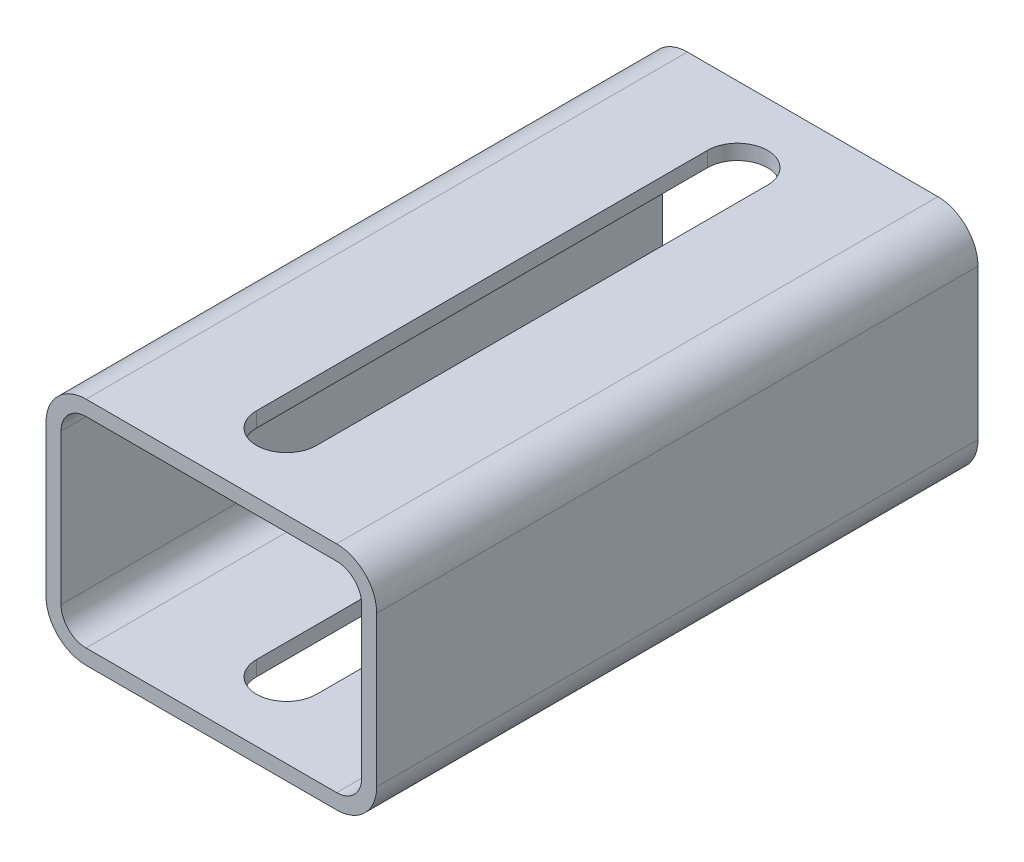
SolidWorks part; units mm, degrees
ref_plane "Front Plane" through (0, 0, 0) normal (0, 0, 1) x (1, 0, 0)
ref_plane "Top Plane" through (0, 0, 0) normal (0, 1, 0) x (1, 0, 0)
ref_plane "Right Plane" through (0, 0, 0) normal (1, 0, 0) x (0, 0, -1)
sketch "Sketch1" plane through (0, 0, 0) normal (0, 0, 1) x (1, 0, 0)
  line L1 (-25, 20) -> (25, 20)
  line L2 (-30, 15) -> (-30, -15)
  line L3 (-25, -20) -> (25, -20)
  line L4 (30, 15) -> (30, -15)
  line L5 (-30, 20) -> (30, -20) construction
  line L6 (-30, -20) -> (30, 20) construction
  arc A0 (-30, -15) -> (-25, -20) centre (-25, -15) ccw
  arc A1 (25, -20) -> (30, -15) centre (25, -15) ccw
  arc A2 (25, 20) -> (30, 15) centre (25, 15) cw
  arc A3 (-25, 20) -> (-30, 15) centre (-25, 15) ccw
  point P0 (0, 0)
  dimension "D3" = 5
  dimension "Height" = 40
  dimension "Width" = 60
extrude "Extrude-Thin1" add sketch "Sketch1" along normal mid plane 120 thin thin type one direction wall 3
sketch "Sketch3" plane through (0, 23, 0) normal (0, 1, 0) x (1, 0, 0)
  line L0 (0, 45) -> (0, -45) construction
  line L1 (6, 45) -> (6, -45)
  line L2 (-6, 45) -> (-6, -45)
  arc A0 (6, 45) -> (-6, 45) centre (0, 45) ccw
  arc A1 (-6, -45) -> (6, -45) centre (0, -45) ccw
  point P2 (0, 0)
  dimension "D2" = 6
  dimension "D1" = 90
extrude "Cut-Extrude1" cut sketch "Sketch3" against normal through all
